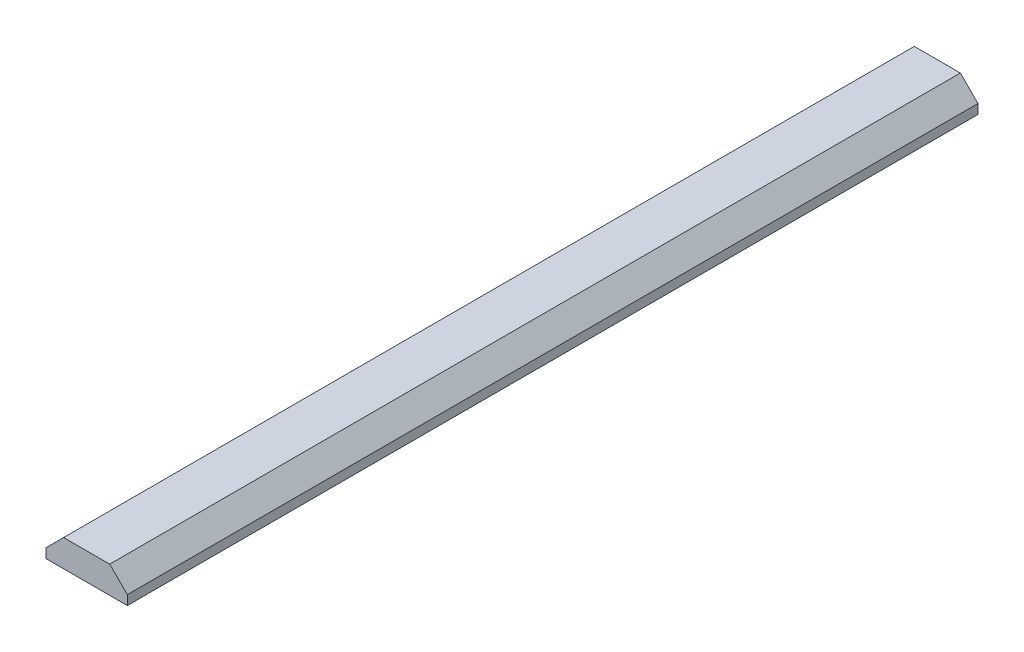
SolidWorks part; units mm, degrees
ref_plane "Ebene vorne" through (0, 0, 0) normal (0, 0, 1) x (1, 0, 0)
ref_plane "Ebene oben" through (0, 0, 0) normal (0, 1, 0) x (1, 0, 0)
ref_plane "Ebene rechts" through (0, 0, 0) normal (1, 0, 0) x (0, 0, -1)
sketch "Skizze1" plane through (0, 0, 0) normal (0, 0, 1) x (1, 0, 0)
  line L0 (0, 0) -> (0, 23680.6173) construction
  line L1 (3.4, 1.8089) -> (-3.4, 1.8089)
  line L2 (-3.4, 1.8089) -> (-6, -0.7911)
  line L3 (-6, -0.7911) -> (-6, -2.1911)
  line L4 (-6, -2.1911) -> (6, -2.1911)
  line L5 (6, -0.7911) -> (6, -2.1911)
  line L6 (3.4, 1.8089) -> (6, -0.7911)
  point P9 (0, -2.1911)
  point P11 (0, 1.8089)
  dimension "D1" = 3.4
  dimension "D2" = 6
  dimension "D3" = 4
  dimension "D4" = 135
extrude "Aufsatz-Linear austragen1" add sketch "Skizze1" along normal blind 125.5 contours L1 L2 L3 L4 L5 L6
